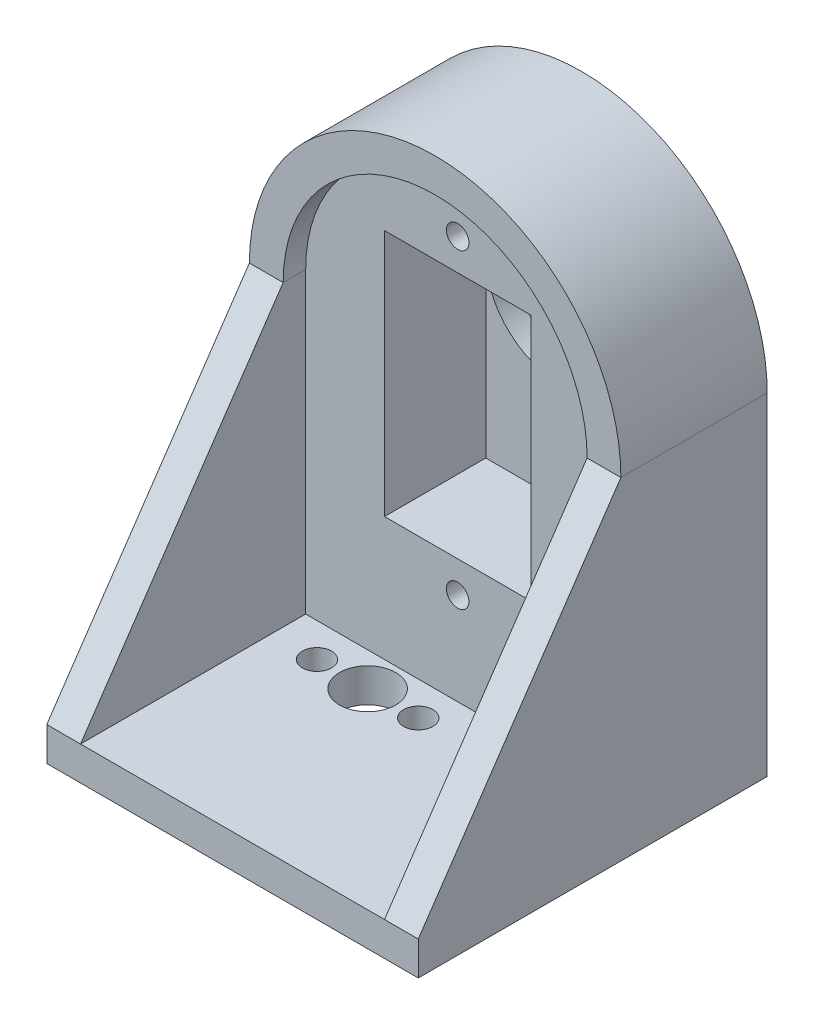
SolidWorks part; units mm, degrees
ref_plane "Front Plane" through (0, 0, 0) normal (0, 0, 1) x (1, 0, 0)
ref_plane "Top Plane" through (0, 0, 0) normal (0, 1, 0) x (1, 0, 0)
ref_plane "Right Plane" through (0, 0, 0) normal (1, 0, 0) x (0, 0, -1)
sketch "Sketch1" plane through (0, 0, 0) normal (0, 0, 1) x (1, 0, 0)
  line L0 (-16.5, 0) -> (-16.5, -29.5)
  line L1 (-16.5, -29.5) -> (16.5, -29.5)
  line L2 (16.5, -29.5) -> (16.5, 0)
  arc A0 (16.5, 0) -> (-16.5, 0) centre (0, 0) ccw
  circle A1 centre (0, 0) radius 6.5
  dimension "D1" = 33
  dimension "D2" = 13
  dimension "D3" = 29.5
extrude "Boss-Extrude1" add sketch "Sketch1" along normal blind 13
sketch "Sketch2" plane through (0, 0, 13) normal (0, 0, 1) x (1, 0, 0)
  line L5 (-13.5, -26.5) -> (13.5, -26.5)
  line L6 (-13.5, 0) -> (-13.5, -26.5)
  line L7 (-13.5, -26.5) -> (13.5, -26.5)
  line L8 (13.5, -26.5) -> (13.5, 0)
  line L9 (-13.5, 0) -> (-13.5, -26.5)
  line L11 (13.5, -26.5) -> (13.5, 0)
  arc A2 (13.5, 0) -> (-13.5, 0) centre (0, 0) ccw
  arc A3 (13.5, 0) -> (-13.5, 0) centre (0, 0) ccw
  dimension "D1" = 3
extrude "Cut-Extrude1" cut sketch "Sketch2" against normal blind 2
sketch "Sketch3" plane through (0, 0, 11) normal (0, 0, 1) x (1, 0, 0)
  line L0 (0, 6.5) -> (0, 9.3) construction
  line L1 (-6.5, 6.5) -> (6.5, 6.5)
  line L2 (-6.5, 6.5) -> (-6.5, -15.5)
  line L3 (-6.5, -15.5) -> (6.5, -15.5)
  line L4 (6.5, 6.5) -> (6.5, -15.5)
  line L5 (-6.5, -4.5) -> (6.5, -4.5) construction
  circle A0 centre (0, 0) radius 6.5 construction
  circle A1 centre (0, 9.3) radius 1
  circle A2 centre (0, -18.3) radius 1
  dimension "D3" = 2
  dimension "D1" = 27.6
  dimension "D2" = 22
extrude "Cut-Extrude2" cut sketch "Sketch3" against normal blind 9
sketch "Sketch4" plane through (0, 0, 13) normal (0, 0, 1) x (1, 0, 0)
  line L0 (-16.5, -29.5) -> (16.5, -29.5)
  line L1 (16.5, -29.5) -> (16.5, -26.5)
  line L2 (16.5, -29.5) -> (16.5, 0) construction
  line L3 (16.5, -26.5) -> (-16.5, -26.5)
  line L4 (-16.5, 0) -> (-16.5, -29.5) construction
  line L5 (-16.5, -26.5) -> (-16.5, -29.9502)
  line M4 (13.5, -26.5) -> (-13.5, -26.5)
  line M7 (-16.5, 0) -> (-16.5, -29.5)
  line M8 (-16.5, -29.5) -> (16.5, -29.5)
  line M9 (16.5, -29.5) -> (16.5, 0)
  dimension "D1" = 3
extrude "Boss-Extrude2" add sketch "Sketch4" along normal blind 18 contours L3 M9 M4 M7 M8
ref_plane "Plane1" through (-15, 0, 0) normal (1, 0, 0) x (0, 0, -1)
sketch "Sketch5" plane through (-15, 0, 0) normal (1, 0, 0) x (0, 0, -1)
  line L0 (-13, 0) -> (-31, -26.5)
  line L1 (-13, 0) -> (-13, -26.5)
  line L2 (-13, -26.5) -> (-31, -26.5)
extrude "Boss-Extrude3" add sketch "Sketch5" along normal mid plane 3
ref_plane "Plane2" through (15, 0, 0) normal (1, 0, 0) x (0, 0, -1)
sketch "Sketch6" plane through (15, 0, 0) normal (1, 0, 0) x (0, 0, -1)
  line L0 (-13, 0) -> (-31, -26.5)
  line L1 (-31, -26.5) -> (-13, -26.5)
  line L2 (-13, -26.5) -> (-13, 0)
extrude "Boss-Extrude4" add sketch "Sketch6" along normal mid plane 3
sketch "Sketch7" plane through (0, -29.5, 0) normal (0, -1, 0) x (1, 0, 0)
  line L0 (-9.5, 14) -> (-0.5, 14) construction
  line L1 (-16.5, 0) -> (16.5, 0) construction
  line L2 (-16.5, 31) -> (-16.5, 0) construction
  circle A0 centre (-5, 14) radius 2.5
  circle A1 centre (-0.5, 14) radius 1.3
  circle A2 centre (-9.5, 14) radius 1.3
  dimension "D1" = 2.6
  dimension "D4" = 9
  dimension "D5" = 5
  dimension "D2" = 14
  dimension "D3" = 11.5
extrude "Cut-Extrude3" cut sketch "Sketch7" against normal blind 5
ref_point "Point1"
ref_point "Point2"
